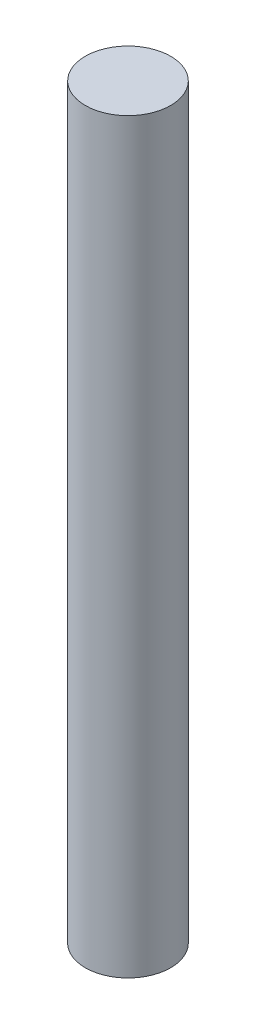
SolidWorks part; units mm, degrees
material "1.5714 (16NiCr4)"
ref_plane "Plan de face" through (0, 0, 0) normal (0, 0, 1) x (1, 0, 0)
ref_plane "Plan de dessus" through (0, 0, 0) normal (0, 1, 0) x (1, 0, 0)
ref_plane "Plan de droite" through (0, 0, 0) normal (1, 0, 0) x (0, 0, -1)
sketch "Esquisse1" plane through (0, 0, 0) normal (0, 1, 0) x (1, 0, 0)
  circle A0 centre (0, 0) radius 4
  dimension "D1" = 8
extrude "Boss.-Extru.1" add sketch "Esquisse1" along normal mid plane 70
